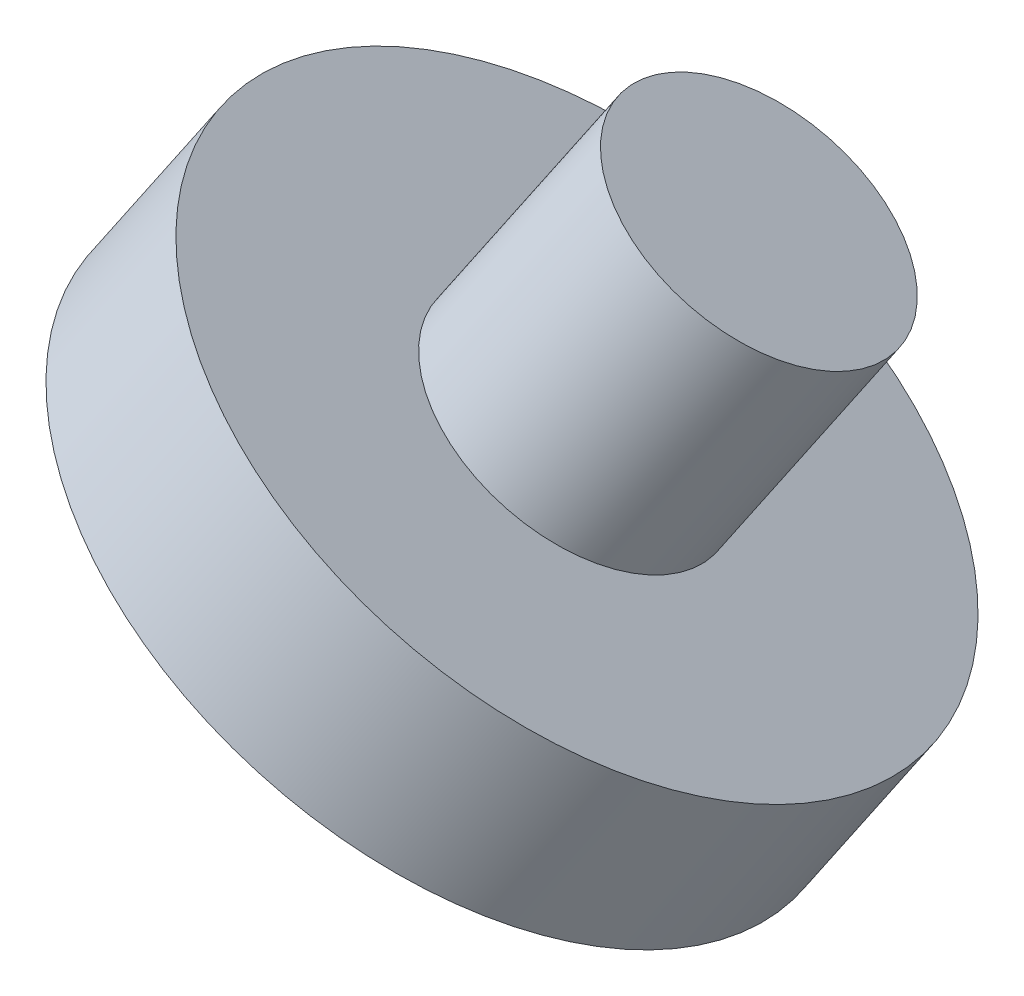
SolidWorks part; units mm, degrees
ref_plane "Front Plane" through (0, 0, 0) normal (0, 0, 1) x (1, 0, 0)
ref_plane "Top Plane" through (0, 0, 0) normal (0, 1, 0) x (1, 0, 0)
ref_plane "Right Plane" through (0, 0, 0) normal (1, 0, 0) x (0, 0, -1)
sketch "Sketch1" plane through (-109.4345, -193.4529, 69.6849) normal (0.4698, 0.8305, -0.2992) x (0.8794, -0.4698, 0.0768)
  circle A0 centre (52.9877, -483.5449) radius 10
extrude "Boss-Extrude1" add sketch "Sketch1" along normal blind 5
sketch "Sketch2" plane through (-107.0854, -189.3003, 68.189) normal (0.4698, 0.8305, -0.2992) x (0.8794, -0.4698, 0.0768)
  circle A0 centre (52.9877, -483.5449) radius 3.95
extrude "Boss-Extrude2" add sketch "Sketch2" along normal blind 7 contours A0
